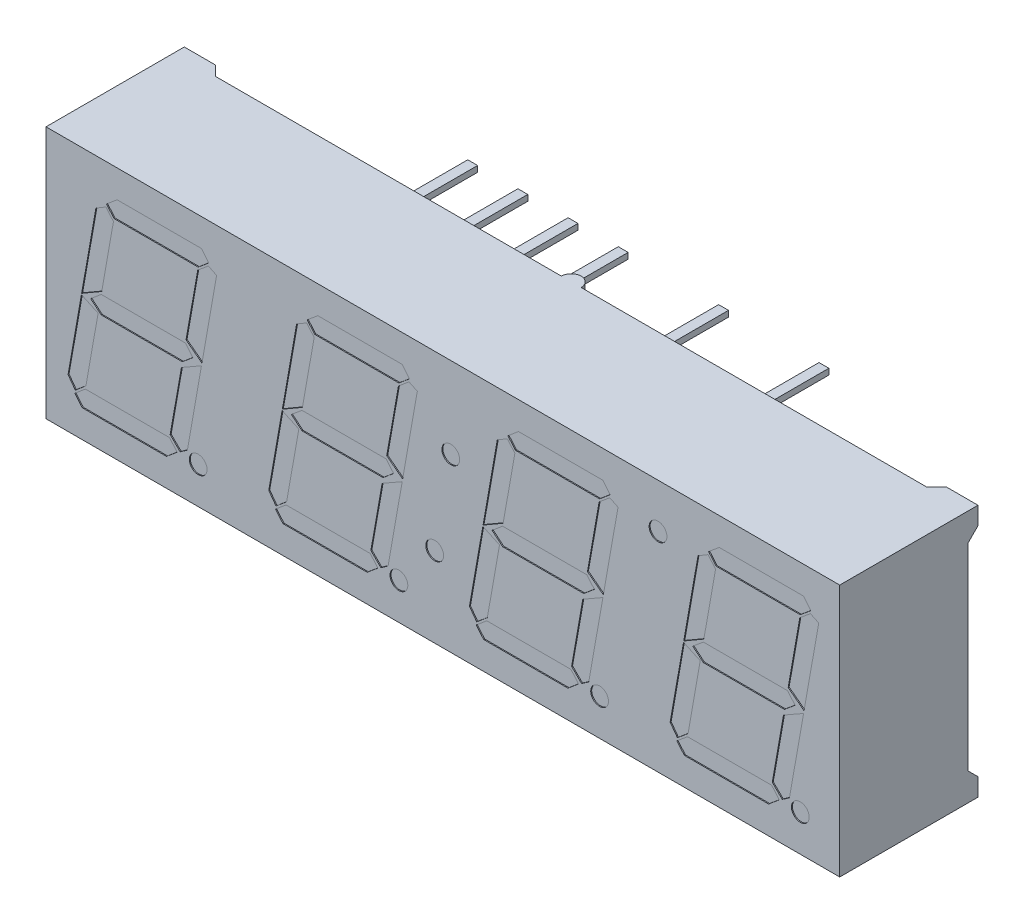
SolidWorks part; units mm, degrees
ref_plane "Front Plane" through (0, 0, 0) normal (0, 0, 1) x (1, 0, 0)
ref_plane "Top Plane" through (0, 0, 0) normal (0, 1, 0) x (1, 0, 0)
ref_plane "Right Plane" through (0, 0, 0) normal (1, 0, 0) x (0, 0, -1)
sketch "Sketch1" plane through (0, 0, 0) normal (0, 0, 1) x (1, 0, 0)
  line L0 (0, 21.8807) -> (0, -21.8807) construction
  line L1 (-40.2007, 0) -> (40.2007, 0) construction
  line L3 (-20.09, 6.4) -> (20.09, 6.4)
  line L4 (-20.09, 6.4) -> (-20.09, -6.4)
  line L5 (-20.09, -6.4) -> (20.09, -6.4)
  line L6 (20.09, 6.4) -> (20.09, -6.4)
  dimension "D1" = 40.18
  dimension "D2" = 12.8
extrude "Extrude1" add sketch "Sketch1" along normal blind 7
sketch "Sketch2" plane through (0, -6.4, 0) normal (0, -1, 0) x (1, 0, 0)
  line L0 (0, 8.7892) -> (0, -2.8828) construction
  line L1 (18, 0.5) -> (19, -0.5)
  line L2 (18, 0.5) -> (0.5, 0.5)
  line L3 (-20.09, 0) -> (20.09, 0) construction
  line L4 (19, -0.5) -> (19, -1.5)
  line L5 (19, -1.5) -> (-19, -1.5)
  line L6 (-19, -0.5) -> (-19, -1.5)
  line L7 (-18, 0.5) -> (-0.5, 0.5)
  line L8 (-18, 0.5) -> (-19, -0.5)
  arc A0 (-0.5, 0.5) -> (0.5, 0.5) centre (0, 0.5) ccw
  point P13 (0, -1.5)
  dimension "D6" = 0.5
  dimension "D1" = 18
  dimension "D2" = 135
  dimension "D3" = 0.5
  dimension "D4" = 19
  dimension "D5" = 2
extrude "Cut-Extrude1" cut sketch "Sketch2" against normal through all
sketch "Sketch3" plane through (20.09, 0, 0) normal (1, 0, 0) x (0, 0, -1)
  line L1 (-0.5, 5) -> (-0.5, -5)
  line L2 (0, 0) -> (-7.4176, 0) construction
  line L3 (-0.5, 5) -> (0.5, 6)
  line L4 (0, -6.4) -> (0, 6.4) construction
  line L5 (-0.5, -5) -> (0.5, -6)
  line L6 (0.5, 6) -> (0.5, -6)
  point P10 (-0.5, 0)
  dimension "D1" = 135
  dimension "D2" = 0.5
  dimension "D3" = 5
  dimension "D4" = 1
extrude "Cut-Extrude2" cut sketch "Sketch3" against normal through all
sketch "Sketch4" plane through (0, -6.4, 0) normal (0, -1, 0) x (1, 0, 0)
  circle A0 centre (0, 0.5) radius 0.5
  arc A1 (-0.5, 0.5) -> (0.5, 0.5) centre (0, 0.5) ccw construction
extrude "Extrude3" add sketch "Sketch4" against normal up to surface (12.8 mm away) up to face at (0, 6.4, 1.55)
sketch "Sketch5" plane through (0, 0, 7) normal (0, 0, 1) x (1, 0, 0)
  line L0 (0, 8.651) -> (0, -8.0683) construction
  line L1 (-15.24, 8.651) -> (-15.24, -8.0683) construction
  line L2 (0, 0) -> (-21.1568, 0) construction
  line L3 (-21.1568, 5) -> (20.843, 5) construction
  line L4 (-21.1568, -5) -> (20.843, -5) construction
  line L5 (-13.7924, 8.2099) -> (-16.6876, -8.2099) construction
  line L6 (-10.7443, 8.2199) -> (-13.6119, -8.0429) construction
  line L7 (-16.8341, 8.2357) -> (-19.5965, -7.4306) construction
  line L8 (-11.6307, 8.3762) -> (-14.4982, -7.8866) construction
  line L9 (-15.9478, 8.0794) -> (-18.7102, -7.5869) construction
  line L10 (-21.1568, 4.1) -> (20.843, 4.1) construction
  line L11 (-21.1568, -4.1) -> (20.843, -4.1) construction
  line L12 (0, 0.45) -> (-21.1568, 0.45) construction
  line L13 (0, -0.45) -> (-21.1568, -0.45) construction
  line L14 (-16.4908, 5) -> (-12.226, 5)
  line L15 (-16.6495, 4.1) -> (-12.3847, 4.1)
  line L16 (-17.293, 0.45) -> (-13.0283, 0.45)
  line L17 (-17.293, -0.45) -> (-13.187, -0.45)
  line L18 (-18.0953, -4.1) -> (-13.8305, -4.1)
  line L19 (-18.254, -5) -> (-13.9892, -5)
  line L20 (-12.3847, 4.1) -> (-11.8484, 4.55)
  line L21 (-11.8484, 4.55) -> (-12.226, 5)
  line L22 (-11.8484, 4.55) -> (-19.2293, 4.55) construction
  line L23 (-12.996, -4.55) -> (-21.1568, -4.55) construction
  line L24 (-16.4908, 5) -> (-17.0271, 4.55)
  line L25 (-17.0271, 4.55) -> (-16.6495, 4.1)
  line L26 (-17.293, 0.45) -> (-17.8293, 0)
  line L27 (-17.8293, 0) -> (-17.293, -0.45)
  line L28 (-13.0283, 0.45) -> (-12.6507, 0)
  line L29 (-12.6507, 0) -> (-13.187, -0.45)
  line L30 (-13.8305, -4.1) -> (-13.4529, -4.55)
  line L31 (-13.4529, -4.55) -> (-13.9892, -5)
  line L32 (-18.0953, -4.1) -> (-18.6316, -4.55)
  line L33 (-18.6316, -4.55) -> (-18.254, -5)
  line L34 (-16.6755, 3.9523) -> (-17.0531, 4.4023)
  line L35 (-16.6755, 3.9523) -> (-17.2683, 0.5905)
  line L36 (-17.2683, 0.5905) -> (-18.2863, 0)
  line L37 (-18.2863, 0) -> (-17.5633, 4.1)
  line L38 (-18.2971, -0.0615) -> (-17.4517, -0.45)
  line L39 (-17.4517, -0.45) -> (-18.0693, -3.9523)
  line L40 (-18.0693, -3.9523) -> (-18.6056, -4.4023)
  line L41 (-18.9744, -3.9023) -> (-18.2971, -0.0615)
  line L42 (-11.1875, 8.298) -> (-14.0551, -7.9648) construction
  line L43 (-16.3909, 8.1576) -> (-19.1533, -7.5087) construction
  line L44 (-17.0531, 4.4023) -> (-17.5633, 4.1)
  line L45 (-18.6056, -4.4023) -> (-18.9744, -3.9023)
  line L46 (-16.1694, 8.1185) -> (-18.9317, -7.5478) construction
  line L47 (-17.293, -0.45) -> (-17.293, 2.2825) construction
  line L48 (-13.0283, 0.45) -> (-13.0283, -1.0482) construction
  line L49 (-17.068, -0.5779) -> (-17.068, 0.8081) construction
  line L50 (-12.4099, 3.9567) -> (-13.0013, 0.6028)
  line L51 (-13.0013, 0.6028) -> (-12.1956, -0.0106)
  line L52 (-12.2188, -0.1425) -> (-12.934, -4.1982)
  line L53 (-12.1956, -0.0106) -> (-11.4524, 4.2043)
  line L54 (-11.4524, 4.2043) -> (-11.8736, 4.4067)
  line L55 (-11.8736, 4.4067) -> (-12.4099, 3.9567)
  line L56 (-12.934, -4.1982) -> (-13.2994, -4.4541)
  line L57 (-13.2994, -4.4541) -> (-13.8045, -3.9523)
  line L58 (-13.8045, -3.9523) -> (-13.235, -0.7227)
  line L59 (-13.235, -0.7227) -> (-12.2188, -0.1425)
  circle A0 centre (-12.3847, -4.55) radius 0.45
  point P13 (-15.24, 0)
  dimension "D1" = 15.24
  dimension "D2" = 10
  dimension "D3" = 10
  dimension "D4" = 6
  dimension "D5" = 3
  dimension "D12" = 0.45
  dimension "D13" = 0.45
  dimension "D16" = 0.15
  dimension "D17" = 0.15
  dimension "D18" = 0.5
  dimension "D20" = 0.225
  dimension "D6" = 0.9
  dimension "D7" = 0.9
  dimension "D8" = 0.9
  dimension "D9" = 0.9
  dimension "D10" = 0.45
  dimension "D11" = 0.45
  dimension "D14" = 0.45
  dimension "D15" = 0.45
  dimension "D19" = 0.225
extrude "Cut-Extrude3" cut sketch "Sketch5" against normal blind 0.05
pattern_linear "LPattern1" count 4 spacing 10.16 along (1, 0, 0) of "Cut-Extrude3"
sketch "Sketch7" plane through (0, 0, 7) normal (0, 0, 1) x (1, 0, 0)
  line L0 (-3.3598, -2.3375) -> (6.8002, -2.3375) construction
  line L3 (-3.075, -0.7227) -> (-3.6445, -3.9523) construction
  line L7 (7.085, -0.7227) -> (6.5155, -3.9523) construction
  line L8 (-2.5456, 2.2797) -> (7.6144, 2.2797) construction
  line L9 (-2.2499, 3.9567) -> (-2.8413, 0.6028) construction
  line L10 (7.9101, 3.9567) -> (7.3187, 0.6028) construction
  line L11 (-1.2924, 4.2043) -> (2.7567, 4.1) construction
  line L12 (-2.774, -4.1982) -> (1.3456, -3.9023) construction
  line L13 (-0.7142, -4.0503) -> (0.7321, 4.1522) construction
  line L14 (8.8676, 4.2043) -> (12.9167, 4.1) construction
  line L15 (7.386, -4.1982) -> (11.5056, -3.9023) construction
  line L16 (9.4458, -4.0503) -> (10.8921, 4.1522) construction
  circle A0 centre (-0.4122, -2.3375) radius 0.45
  circle A1 centre (0.402, 2.2797) radius 0.45
  circle A2 centre (10.8921, 4.1522) radius 0.45
  circle A3 centre (-2.2247, -4.55) radius 0.45 construction
  point P40 (0, 0)
extrude "L Features" cut sketch "Sketch7" against normal up to surface (0.05 mm away) up to face at (5.8823, 4.55, 6.95)
sketch "Sketch6" plane through (0, 0, 0.5) normal (0, 0, -1) x (-1, 0, 0)
  line L0 (0, 9.2785) -> (0, -8.2027) construction
  line L1 (-8.89, 8.5732) -> (-8.89, -8.2357) construction
  line L2 (-12.2817, 0) -> (6.1857, 0) construction
  line L3 (-11.7886, 5.08) -> (5.7823, 5.08) construction
  line L4 (-8.64, -5.23) -> (-8.64, -4.93)
  line L5 (-9.14, 5.23) -> (-8.64, 5.23)
  line L6 (-9.14, 5.23) -> (-9.14, 4.93)
  line L7 (-9.14, 4.93) -> (-8.64, 4.93)
  line L8 (-8.64, 5.23) -> (-8.64, 4.93)
  line L9 (-9.14, -4.93) -> (-8.64, -4.93)
  line L10 (-9.14, -5.23) -> (-9.14, -4.93)
  line L11 (-9.14, -5.23) -> (-8.64, -5.23)
  dimension "D3" = 0.5
  dimension "D1" = 8.89
  dimension "D2" = 5.08
  dimension "D4" = 0.3
extrude "Extrude4" add sketch "Sketch6" along normal blind 3.9
pattern_linear "LPattern2" count 8 spacing 2.54 along (-1, 0, 0) of "Extrude4"
sketch "Sketch8" plane through (0, 0, -3.4) normal (0, 0, -1) x (-1, 0, 0)
  line L1 (-6.6, 5.23) -> (-6.1, 5.23)
  line L2 (-6.6, 5.23) -> (-6.6, 4.93)
  line L3 (-6.6, 4.93) -> (-6.1, 4.93)
  line L4 (-6.1, 5.23) -> (-6.1, 4.93)
  line L5 (-1.52, 5.23) -> (-1.02, 5.23)
  line L6 (-1.52, 5.23) -> (-1.52, 4.93)
  line L7 (-1.52, 4.93) -> (-1.02, 4.93)
  line L8 (-1.02, 5.23) -> (-1.02, 4.93)
extrude "NC Pin Remove" cut sketch "Sketch8" against normal up to surface (3.9 mm away) up to face at (1.27, 5.08, 0.5)
